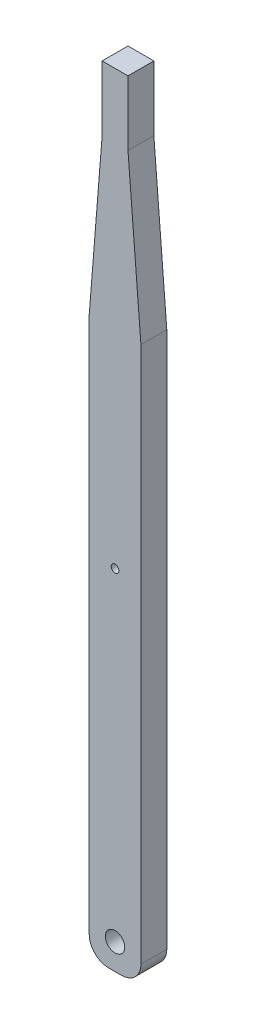
SolidWorks part; units mm, degrees
material "Custom Plastic"
ref_plane "Front Plane" through (0, 0, 0) normal (0, 0, 1) x (1, 0, 0)
ref_plane "Top Plane" through (0, 0, 0) normal (0, 1, 0) x (1, 0, 0)
ref_plane "Right Plane" through (0, 0, 0) normal (1, 0, 0) x (0, 0, -1)
sketch "Sketch1" plane through (0, 0, 0) normal (0, 0, 1) x (1, 0, 0)
  line L1 (4, -60.5) -> (-4, -60.5)
  line L2 (4, -60.5) -> (4, 60.5)
  line L3 (4, 60.5) -> (-4, 60.5)
  line L4 (-4, -60.5) -> (-4, 60.5)
  line L5 (4, -60.5) -> (-4, 60.5) construction
  line L6 (4, 60.5) -> (-4, -60.5) construction
  point P0 (0, 0)
  dimension "D1" = 121
  dimension "D2" = 8
extrude "Boss-Extrude1" add sketch "Sketch1" along normal blind 4
fillet "Fillet1" radius 3 2 edges at (4, -60.5, 2) (-4, -60.5, 2)
sketch "Sketch2" plane through (0, 0, 4) normal (0, 0, 1) x (1, 0, 0)
  line L0 (-4, 25.5) -> (-2, 50.5)
  line L1 (-4, 60.5) -> (-4, -57.5) construction
  line L2 (-2, 50.5) -> (-2, 60.5)
  line L3 (4, 60.5) -> (-4, 60.5) construction
  line L4 (-2, 60.5) -> (2, 60.5) construction
  line L5 (2, 60.5) -> (2, 50.5)
  line L6 (2, 50.5) -> (4, 25.5)
  line L7 (4, -57.5) -> (4, 60.5) construction
  line L8 (-4, 25.5) -> (-4, 60.5)
  line L9 (-4, 60.5) -> (-2, 60.5)
  line L10 (2, 60.5) -> (4, 60.5)
  line L11 (4, 60.5) -> (4, 25.5)
  point P4 (0, 60.5)
  dimension "D1" = 4
  dimension "D2" = 10
  dimension "D3" = 25
extrude "Cut-Extrude1" cut sketch "Sketch2" against normal up to surface (4 mm away) up to face at (0, -19.3738, 0)
hole_wizard "Ø1.0mm Dowel Hole1" positions "Sketch3" profile "Sketch5" hole size "Ø1.0" standard "ANSI Metric"
sketch "Sketch3" plane through (0, 0, 4) normal (0, 0, 1) x (1, 0, 0)
  line L0 (-1, -60.5) -> (1, -60.5) construction
  point P0 (0, -56.5)
  point P6 (0, -60.5)
  dimension "D1" = 4
sketch "Sketch5" plane through (0, -56.5, 4) normal (1, 0, 0) x (0, -1, 0)
  line L0 (0, 0) -> (0, 3.999)
  line L1 (0, 3.999) -> (1.5, 3.999)
  line L2 (1.5, 3.999) -> (1.5, 0)
  line L5 (1.5, 0) -> (0, 0)
  line L10 (0, 3.999) -> (-1.5, 3.999) construction
  line L11 (0, -6.35) -> (0, 107.95) construction
  dimension "Hole Dia." = 3
  dimension "Hole Depth" = 3.999
  dimension "Drill Angle" = 180
sketch "Sketch6" plane through (0, 0, 4) normal (0, 0, 1) x (1, 0, 0)
  circle A0 centre (0, -6.5) radius 0.6
  circle A1 centre (0, -56.5) radius 1.5 construction
  dimension "D1" = 50
  dimension "D2" = 1.2
extrude "Cut-Extrude2" cut sketch "Sketch6" against normal blind 10
